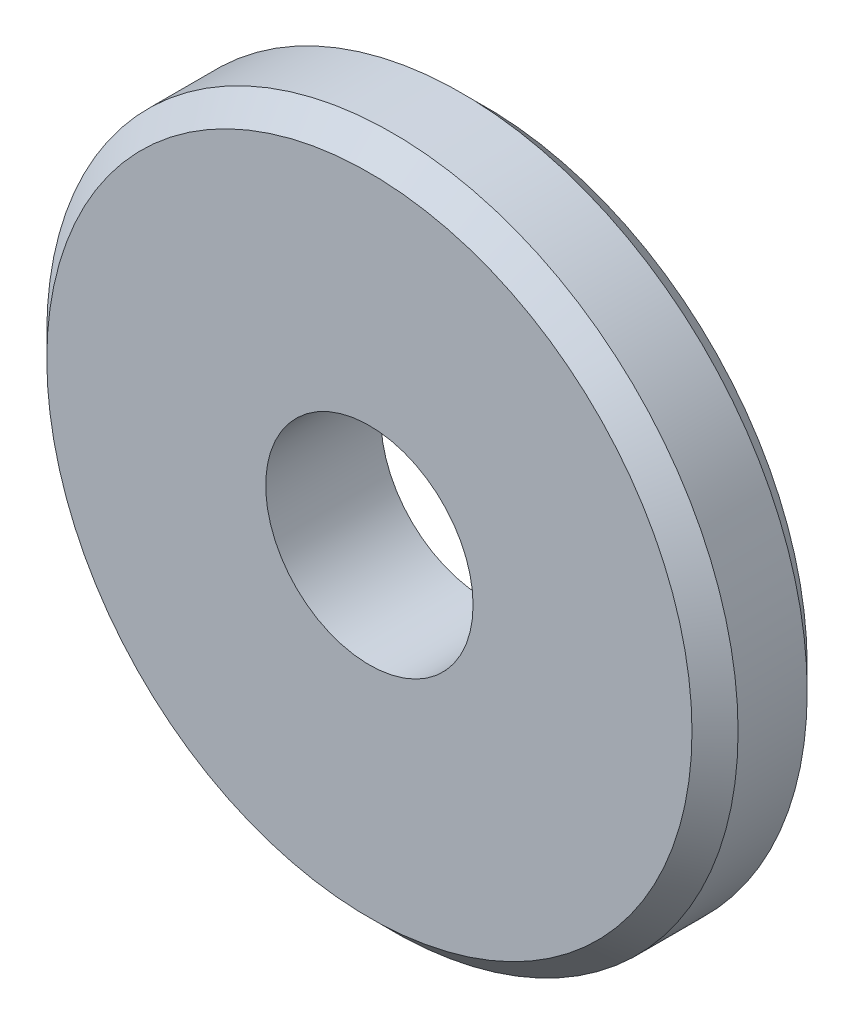
SolidWorks part; units mm, degrees
ref_plane "Front Plane" through (0, 0, 0) normal (0, 0, 1) x (1, 0, 0)
ref_plane "Top Plane" through (0, 0, 0) normal (0, 1, 0) x (1, 0, 0)
ref_plane "Right Plane" through (0, 0, 0) normal (1, 0, 0) x (0, 0, -1)
sketch "Sketch1" plane through (0, 0, 0) normal (0, 0, 1) x (1, 0, 0)
  circle A0 centre (0, 0) radius 15
  circle A1 centre (0, 0) radius 4.5
  dimension "D1" = 30
  dimension "D2" = 9
extrude "Boss-Extrude1" add sketch "Sketch1" along normal blind 5 contours A0 | A1
chamfer "Chamfer1" distance 1 angle 45 2 edges at (15, 0, 5) (15, 0, 0)
